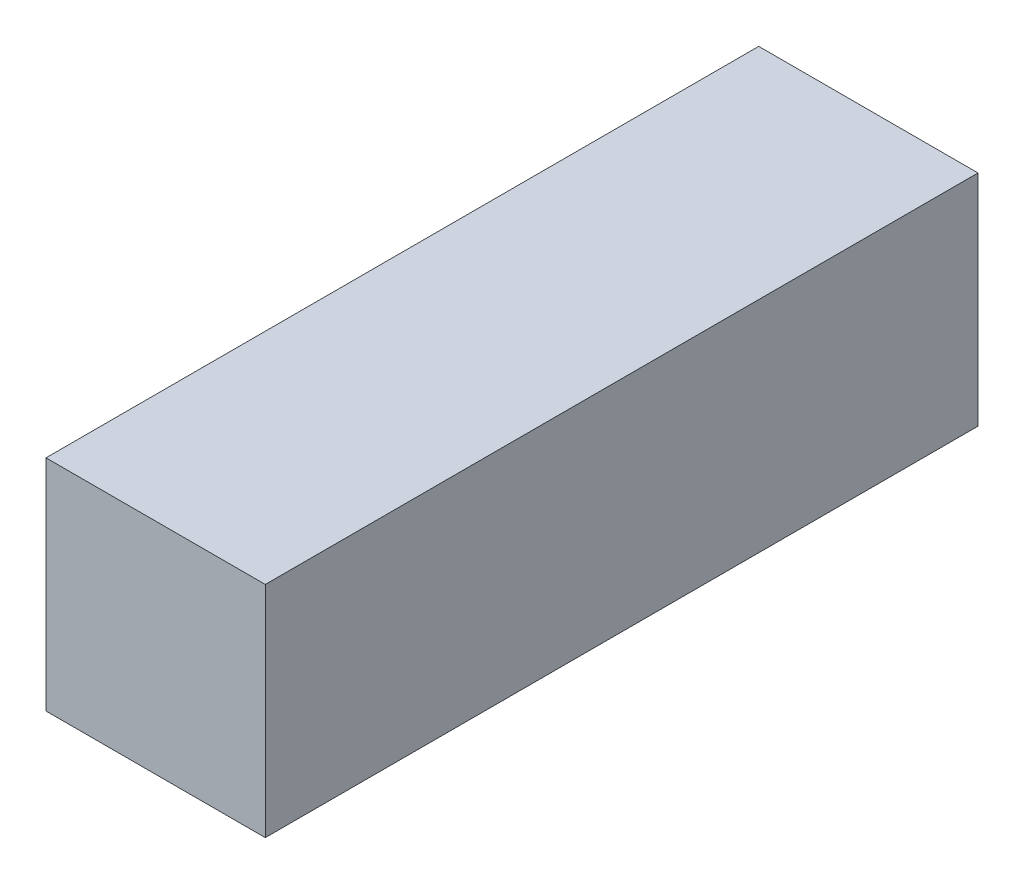
SolidWorks part; units mm, degrees
ref_plane "Front" through (0, 0, 0) normal (0, 0, 1) x (1, 0, 0)
ref_plane "Top" through (0, 0, 0) normal (0, 1, 0) x (1, 0, 0)
ref_plane "Right" through (0, 0, 0) normal (1, 0, 0) x (0, 0, -1)
sketch "Sketch1" plane through (0, 0, 0) normal (0, 0, 1) x (1, 0, 0)
  line L1 (-10, 10) -> (10, 10)
  line L2 (-10, 10) -> (-10, -10)
  line L3 (-10, -10) -> (10, -10)
  line L4 (10, 10) -> (10, -10)
  dimension "D1" = 20
  dimension "D2" = 20
  dimension "D3" = 10
  dimension "D4" = 10
extrude "Boss-Extrude1" add sketch "Sketch1" along normal blind 65
